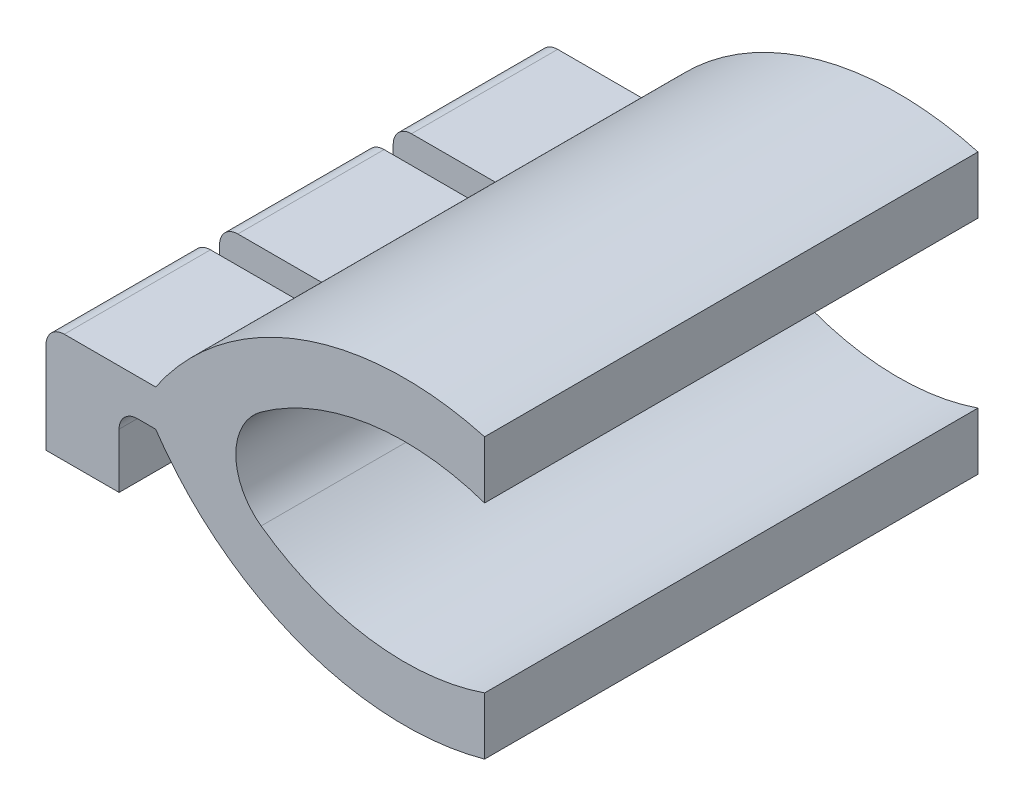
SolidWorks part; units mm, degrees
ref_plane "Plan de face" through (0, 0, 0) normal (0, 0, 1) x (1, 0, 0)
ref_plane "Plan de dessus" through (0, 0, 0) normal (0, 1, 0) x (1, 0, 0)
ref_plane "Plan de droite" through (0, 0, 0) normal (1, 0, 0) x (0, 0, -1)
sketch "Esquisse1" plane through (0, 0, 0) normal (0, 0, 1) x (1, 0, 0)
  line L0 (0, 0) -> (-21.2687, 0) construction
  line L1 (-12.7341, 1) -> (-18.7341, 1)
  line L2 (-18.7341, 1) -> (-18.7341, -5)
  line L3 (-18.7341, -5) -> (-14.7341, -5)
  line L4 (-14.7341, -5) -> (-14.7341, -1)
  line L5 (-14.7341, -1) -> (-12.7341, -1)
  line L6 (5.2659, 4.5) -> (5.2659, 7.6386)
  line L7 (5.2659, -4.5) -> (5.2659, -7.6386)
  arc A0 (5.2659, 7.6386) -> (-12.7341, 1) centre (0.8941, -8.2298) ccw
  arc A1 (5.2659, -7.6386) -> (-12.7341, -1) centre (0.8941, 8.2298) cw
  arc A2 (5.2659, 4.5) -> (-6.9613, 2.6996) centre (0.8941, -8.2298) ccw
  arc A3 (5.2659, -4.5) -> (-6.9613, -2.6996) centre (0.8941, 8.2298) cw
  arc A4 (-6.9613, -2.6996) -> (-6.9613, 2.6996) centre (-5.0209, 0) cw
  point P0 (0.8941, -8.2298)
  point P10 (0.8941, 8.2298)
  point P20 (0, 0)
  point P21 (5.3397, -1.9095)
  point P22 (7.5584, -1.995)
  point P23 (8.2494, -6.4394)
  point P24 (0.3201, 7.721)
  point P25 (0, 0)
  dimension "D1" = 18
  dimension "D7" = 3
  dimension "D3" = 2
  dimension "D4" = 2
  dimension "D5" = 6
  dimension "D6" = 4
  dimension "D8" = 9
extrude "Boss.-Extru.1" add sketch "Esquisse1" along normal blind 27
sketch "Esquisse2" plane through (-18.7341, 0, 0) normal (-1, 0, 0) x (0, 0, 1)
  line L5 (8, -8.9763) -> (8, 11.0237)
  line L6 (8, 11.0237) -> (9.5, 11.0237)
  line L10 (19, -9) -> (19, 11)
  line L11 (9.5, 11.0237) -> (9.5, -8.9763)
  line L12 (9.5, -8.9763) -> (8, -8.9763)
  line L15 (19, 11) -> (17.5, 11)
  line L16 (17.5, 11) -> (17.5, -9)
  line L17 (17.5, -9) -> (19, -9)
  line L27 (27, 1) -> (27, 8.2298) construction
  line L33 (27, 1) -> (0, 1) construction
  point P7 (10.1845, 1.0668)
  point P9 (19, -9)
  point P13 (0, -4.0752)
  point P19 (25.4547, 1.0431)
  point P21 (0, -7.9134)
  point P27 (0, -4.0752)
  point P31 (13.9212, 10.6848)
  dimension "D7" = 10
  dimension "D2" = 8
  dimension "D3" = 1.5
  dimension "D4" = 8
  dimension "D5" = 8
  dimension "D12" = 1.5
extrude "Enlèv. mat.-Extru.3" cut sketch "Esquisse2" against normal blind 6
fillet "Congé1" radius 1 6 edges at (-18.7341, 1, 4) (-14.7341, -1, 4) (-18.7341, 1, 23) (-18.7341, 1, 13.5) (-14.7341, -1, 23) (-14.7341, -1, 13.5)
